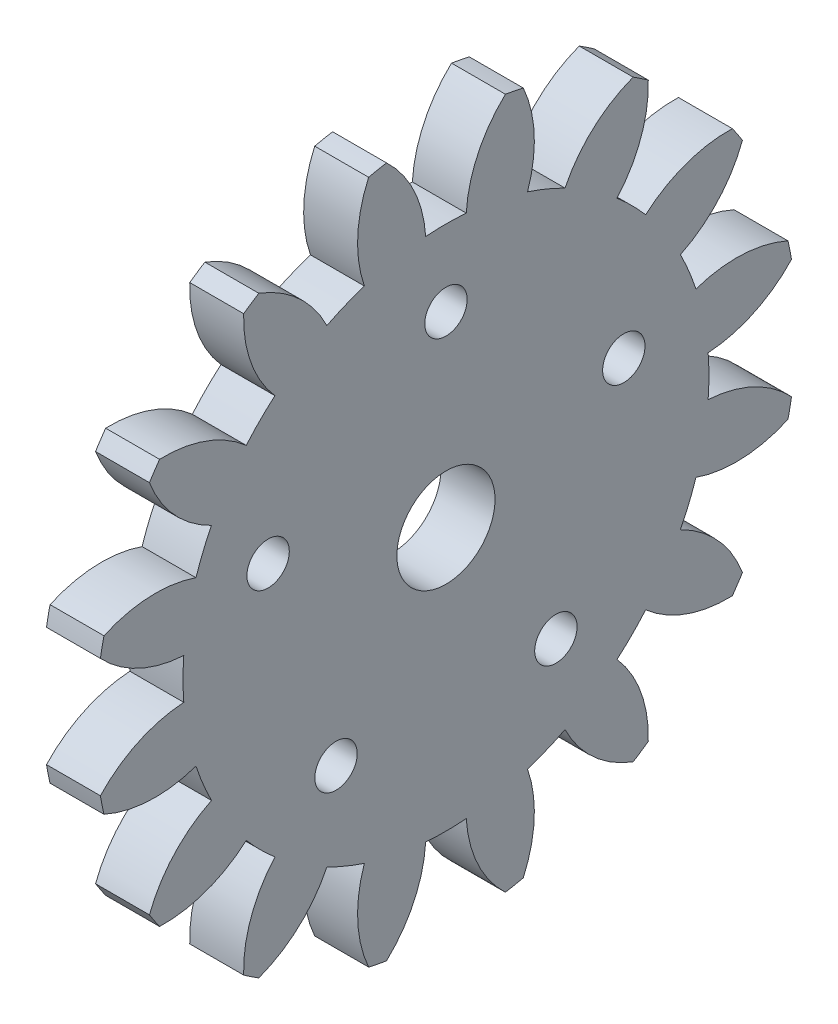
SolidWorks part; units mm, degrees
ref_plane "Plane1" through (0, 0, 0) normal (0, 0, 1) x (1, 0, 0)
ref_plane "Plane2" through (0, 0, 0) normal (0, 1, 0) x (1, 0, 0)
ref_plane "Plane3" through (0, 0, 0) normal (1, 0, 0) x (0, 0, -1)
sketch "HoldingSke" plane through (0, 0, 0) normal (0, 1, 0) x (1, 0, 0)
  line L0 (0, 0) -> (195.3284, -56.0095)
  line L1 (-15, 0) -> (100, 0) construction
  line L2 (0, 0) -> (-2.1039, 2.3779)
  line L3 (0, 0) -> (-11.863, 4.5341)
  line L4 (0, 0) -> (8.3015, 2.3804)
  line L5 (0, 0) -> (-47.5972, -17.7524)
  line L6 (0, 0) -> (-9.7909, -6.6059)
  line L7 (-2.1039, 2.3779) -> (8.8308, 51.9871)
  line L8 (-76.2, 54.61) -> (-75.184, 54.61)
  line L9 (-71.009, 38.7566) -> (-53.1078, 45.2721)
  line L10 (-76.2, 71.12) -> (104.1128, 71.12)
  line L11 (0, 0) -> (-11.811, 0)
  line L12 (-76.2, 101.6) -> (-76.0857, 101.6)
  line L13 (24.9733, 27.94) -> (52.9518, 28.4284)
  line L14 (24.9733, 27.94) -> (24.9746, 27.94)
  line L15 (24.9733, 27.94) -> (100.4006, 29.5858)
  circle A0 centre (0, 0) radius 0.3969
  circle A1 centre (0, 0) radius 21.43
  circle A2 centre (0, 0) radius 38.1
  circle A3 centre (0, 0) radius 0.3969
  dimension "MHD" = 42.86
  dimension "Hub_dia" = 76.2
  dimension "Bore" = 0.7937
  dimension "MBD" = 0.7937
  dimension "Num_teeth" = 16
  dimension "Pitch_radius" = 180.3128
  dimension "Pitch" = 203.2
  dimension "Width" = 11.811
  dimension "Overall_len" = 50.8
  dimension "Show_teeth" = 16
  dimension "Thickness" = 11.811
  dimension "OAL" = 50.8001
  dimension "T_dim" = 1.016
  dimension "Ap" = 20
  dimension "H" = 19.05
  dimension "Backlash" = 0.1143
  dimension "Addendum_fac" = 1
  dimension "Dedendum_fac" = 1.25
  dimension "Clearance_fac" = 0.25
  dimension "Dedendum_add" = 0.0013
sketch "BasProSke" plane through (0, 0, 0) normal (0, 1, 0) x (1, 0, 0)
  line L0 (-10, 0) -> (60, 0) construction
  line L1 (0, 0) -> (0, 28.575)
  line L2 (0, 0) -> (11.811, 0)
  line L3 (11.811, 0) -> (11.811, 28.575)
  line L4 (11.811, 28.575) -> (0, 28.575)
  dimension "Diameter" = 57.15
  dimension "Thickness" = 11.811
revolve "Base-Revolve" add sketch "BasProSke" angle 360 about L0
sketch "TooCutSke" plane through (0, 0, 0) normal (1, 0, 0) x (0, 0, -1)
  line L1 (0, 0) -> (0, 107) construction
  line L2 (0, 0) -> (-2.6895, 25.2572) construction
  line L3 (0, 0) -> (-9.8702, 49.6211) construction
  line L4 (-2.6895, 25.2572) -> (-4.9351, 24.8105) construction
  arc A0 (1.6538, 21.3661) -> (-1.6538, 21.3661) centre (0, 0) ccw
  arc A1 (4.8685, 28.183) -> (-4.8685, 28.183) centre (0, 0) ccw
  circle A2 centre (0, 0) radius 25.4 construction
  circle A3 centre (0, 0) radius 23.8682 construction
  arc A4 (-1.6538, 21.3661) -> (-4.8685, 28.183) centre (-11.7951, 20.7501) ccw
  arc A5 (4.8685, 28.183) -> (1.6538, 21.3661) centre (11.7951, 20.7501) ccw
  dimension "Root_dia" = 42.86
  dimension "Overcut_dia" = 57.2008
  dimension "Pitch_dia" = 50.8
  dimension "Base_dia" = 47.7364
  dimension "Flank_rad" = 10.16
  dimension "Half_ang" = 11.25
  dimension "Half_CT" = 2.2896
extrude "ToothCut" cut sketch "TooCutSke" along normal through all
fillet "Breaks" [suppressed] radius 0.0635
fillet "RootFillets" [suppressed] radius 0.795
pattern_circular "TeethCuts" count 16 every 22.5 about axis through (-10, 0, 0) along (1, 0, 0) of "ToothCut", "RootFillets", "Breaks"
sketch "HubNeaOneSke" plane through (0, 0, 0) normal (-1, 0, 0) x (0, 0, 1)
  circle A0 centre (0, 0) radius 21.43
  dimension "Diameter" = 42.86
extrude "HubNearOne" [suppressed] add sketch "HubNeaOneSke" along normal blind 38.9891
sketch "HubNeaBotSke" plane through (0, 0, 0) normal (-1, 0, 0) x (0, 0, 1)
  circle A0 centre (0, 0) radius 21.43
  dimension "Diameter" = 42.86
extrude "HubNearBoth" [suppressed] add sketch "HubNeaBotSke" along normal blind 19.4945
ref_plane "FarPln" through (11.811, 0, 0) normal (1, 0, 0) x (0, 0, -1)
sketch "HubFarSke" plane through (11.811, 0, 0) normal (1, 0, 0) x (0, 0, -1)
  circle A0 centre (0, 0) radius 21.43
  dimension "Diameter" = 42.86
extrude "HubFar" [suppressed] add sketch "HubFarSke" along normal blind 19.4945
sketch "BorSke" plane through (0, 0, 0) normal (1, 0, 0) x (0, 0, -1)
  circle A0 centre (0, 0) radius 0.3969
  dimension "Diameter" = 0.7937
extrude "Bore" cut sketch "BorSke" along normal mid plane 101.6001
sketch "KeySke" plane through (0, 0, 0) normal (1, 0, 0) x (0, 0, -1)
  line L0 (-0.127, 0) -> (-0.127, 0.6191)
  line L1 (-0.127, 0.6191) -> (0.127, 0.6191)
  line L2 (0.127, 0.6191) -> (0.127, 0)
  line L3 (0, 0) -> (0, 34) construction
  line L4 (-0.127, 0) -> (0.127, 0)
  dimension "Offset" = 0.6191
  dimension "Width" = 0.254
extrude "Keyway" [suppressed] cut sketch "KeySke" along normal mid plane 101.6001
pattern_circular "Keyway2" [suppressed] count 2 every 90 about axis through (-10, 0, 0) along (1, 0, 0)
sketch "Sketch1" plane through (11.811, 0, 0) normal (1, 0, 0) x (0, 0, -1)
  circle A0 centre (0, 0) radius 4
  dimension "D1" = 8
extrude "Cut-Extrude1" cut sketch "Sketch1" against normal through all
sketch "Sketch2" plane through (11.811, 0, 0) normal (1, 0, 0) x (0, 0, -1)
  line L0 (0, 0) -> (0, 25.415) construction
  circle A0 centre (0, 15.24) radius 1.7272
  circle A1 centre (14.4941, 4.7094) radius 1.7272
  circle A2 centre (8.9578, -12.3294) radius 1.7272
  circle A3 centre (-8.9578, -12.3294) radius 1.7272
  circle A4 centre (-14.4941, 4.7094) radius 1.7272
  point P15 (0, 0)
  dimension "D1" = 3.4544
  dimension "D2" = 15.24
  dimension "D3" = 5
extrude "Cut-Extrude2" cut sketch "Sketch2" against normal through all
sketch "Sketch3" plane through (0, 0, 0) normal (-1, 0, 0) x (0, 0, 1)
  line L1 (-38.0473, 36.8869) -> (37.0153, 36.8869)
  line L2 (-38.0473, 36.8869) -> (-38.0473, -31.5164)
  line L3 (-38.0473, -31.5164) -> (37.0153, -31.5164)
  line L4 (37.0153, 36.8869) -> (37.0153, -31.5164)
extrude "Cut-Extrude3" cut sketch "Sketch3" against normal blind 7.4168
equation "' \"Pitch@HoldingSke\" = 4"
equation "' \"Num_teeth@HoldingSke\" = 12"
equation "' \"Ap@HoldingSke\" =  20"
equation "' \"Width@HoldingSke\" = 0.5"
equation "' \"Hub_dia@HoldingSke\"= 1"
equation "' \"Overall_len@HoldingSke\" = 1.0"
equation "' \"Bore@HoldingSke\" = 0.75"
equation "' \"T_dim@HoldingSke\" = 0.85"
equation "' \"Width@KeySke\" = 0.25"
equation "' \"Show_teeth@HoldingSke\" = 13"
equation "' \"Backlash@HoldingSke\" = 0.009"
equation "' \"Addendum_fac@HoldingSke\" = 1.0"
equation "' \"Dedendum_fac@HoldingSke\" = 1.25"
equation "' \"Dedendum_add@HoldingSke\" = 0.00005"
equation "' \"Clearance_fac@HoldingSke\" = 0.25"
equation "' \"Pitch@HoldingSke\" = 0.5"
equation "' \"Num_teeth@HoldingSke\" = 23"
equation "' \"Show_teeth@HoldingSke\" = 23"
equation "' \"Backlash@HoldingSke\" = 0.0375"
equation "\"Overcut_dia@TooCutSke\" = (\"Num_teeth@HoldingSke\" + 2 * \"Addendum_fac@HoldingSke\") / \"Pitch@HoldingSke\" + 0.002"
equation "\"Pitch_dia@TooCutSke\" = \"Num_teeth@HoldingSke\" / \"Pitch@HoldingSke\""
equation "\"Base_dia@TooCutSke\" = \"Num_teeth@HoldingSke\" / \"Pitch@HoldingSke\" * cos((\"Ap@HoldingSke\"  * 3.14159265 / 180))"
equation "\"Root_dia@TooCutSke\" = (\"Num_teeth@HoldingSke\" + 2) / \"Pitch@HoldingSke\" - 2 * (\"Addendum_fac@HoldingSke\" + \"Dedendum_fac@HoldingSke\") / \"Pitch@HoldingSke\" - \"Dedendum_add@HoldingSke\" * 2"
equation "\"Half_ang@TooCutSke\" = 180 / \"Num_teeth@HoldingSke\""
equation "\"Half_CT@TooCutSke\" = \"Num_teeth@HoldingSke\" / \"Pitch@HoldingSke\" * sin((3.14159265 / 2 / \"Num_teeth@HoldingSke\")) / 2 - 7 * \"Backlash@HoldingSke\" / 4"
equation "\"Flank_rad@TooCutSke\" = \"Num_teeth@HoldingSke\" / \"Pitch@HoldingSke\" / 5"
equation "\"Radius@RootFillets\" = \"Clearance_fac@HoldingSke\" / \"Pitch@HoldingSke\" + \"Dedendum_add@HoldingSke\""
equation "\"Break_rad@Breaks\" = 0.02 / \"Pitch@HoldingSke\""
equation "\"Thickness@HoldingSke\" = \"Width@HoldingSke\""
equation "\"OAL@HoldingSke\" = \"Thickness@HoldingSke\""
equation "\"MHD@HoldingSke\" = (\"Num_teeth@HoldingSke\" + 2) / \"Pitch@HoldingSke\" - 2 * (\"Addendum_fac@HoldingSke\" + \"Dedendum_fac@HoldingSke\")  / \"Pitch@HoldingSke\" - \"Dedendum_add@HoldingSke\" * 2"
equation "\"MBD@HoldingSke\" = (\"Num_teeth@HoldingSke\" + 2) / \"Pitch@HoldingSke\" - 2 * (\"Addendum_fac@HoldingSke\" + \"Dedendum_fac@HoldingSke\")  / \"Pitch@HoldingSke\" - \"Dedendum_add@HoldingSke\" * 2 - 0.002"
equation "\"MHD@HoldingSke\" = ((sgn( \"MHD@HoldingSke\" - \"Hub_dia@HoldingSke\" )-1)*( \"MHD@HoldingSke\" - \"Hub_dia@HoldingSke\" ))/-2+ \"Hub_dia@HoldingSke\""
equation "\"MBD@HoldingSke\" = ((sgn( \"MBD@HoldingSke\" - \"Bore@HoldingSke\" )-1)*( \"MBD@HoldingSke\" - \"Bore@HoldingSke\" ))/-2+ \"Bore@HoldingSke\""
equation "\"OAL@HoldingSke\" = ((sgn( \"OAL@HoldingSke\" - \"Overall_len@HoldingSke\" )+1)*( \"OAL@HoldingSke\" - \"Overall_len@HoldingSke\" ))/2 + \"Overall_len@HoldingSke\" + 0.000002"
equation "\"Num_teeth@TeethCuts\" = int( \"Show_teeth@HoldingSke\" ) + 1"
equation "\"Num_teeth@TeethCuts\" = ((sgn( \"Num_teeth@TeethCuts\" - \"Num_teeth@HoldingSke\" )-1)*( \"Num_teeth@TeethCuts\" - \"Num_teeth@HoldingSke\" ))/-2+ \"Num_teeth@HoldingSke\""
equation "\"Num_teeth@TeethCuts\" = ((sgn( \"Num_teeth@TeethCuts\" - 2.0)+1)*( \"Num_teeth@TeethCuts\" - 2.0))/2 +2.0"
equation "\"Angle@TeethCuts\" = 360.0 / \"Num_teeth@HoldingSke\""
equation "\"Diameter@BasProSke\" = (\"Num_teeth@HoldingSke\" + 2 * \"Addendum_fac@HoldingSke\") / \"Pitch@HoldingSke\""
equation "\"Thickness@BasProSke\"  = \"Thickness@HoldingSke\""
equation "' \"Fillet_rad@BasProSke\" =  \"Thickness@HoldingSke\" * 0.05"
equation "\"MHD@HoldingSke\" = ((sgn( \"MHD@HoldingSke\" - \"Root_dia@TooCutSke\" )-1)*( \"MHD@HoldingSke\" - \"Root_dia@TooCutSke\" ))/-2+ \"Root_dia@TooCutSke\""
equation "\"Diameter@HubNeaOneSke\" = \"MHD@HoldingSke\""
equation "\"Length@HubNearOne\" = \"OAL@HoldingSke\" - \"Thickness@BasProSke\""
equation "\"Diameter@HubNeaBotSke\" = \"MHD@HoldingSke\""
equation "\"Length@HubNearBoth\" = ( \"OAL@HoldingSke\" - \"Thickness@BasProSke\" ) / 2.0"
equation "\"Thickness@FarPln\" = \"Thickness@BasProSke\""
equation "\"Diameter@HubFarSke\" = \"MHD@HoldingSke\""
equation "\"Length@HubFar\" = ( \"OAL@HoldingSke\" - \"Thickness@BasProSke\" ) / 2.0"
equation "\"Diameter@BorSke\" = \"MBD@HoldingSke\""
equation "\"D1@Bore\" = \"OAL@HoldingSke\" * 2.0"
equation "\"D1@Keyway\" = \"OAL@HoldingSke\" * 2.0"
equation "\"Offset@KeySke\" = \"T_dim@HoldingSke\" - \"MBD@HoldingSke\" / 2.0"
